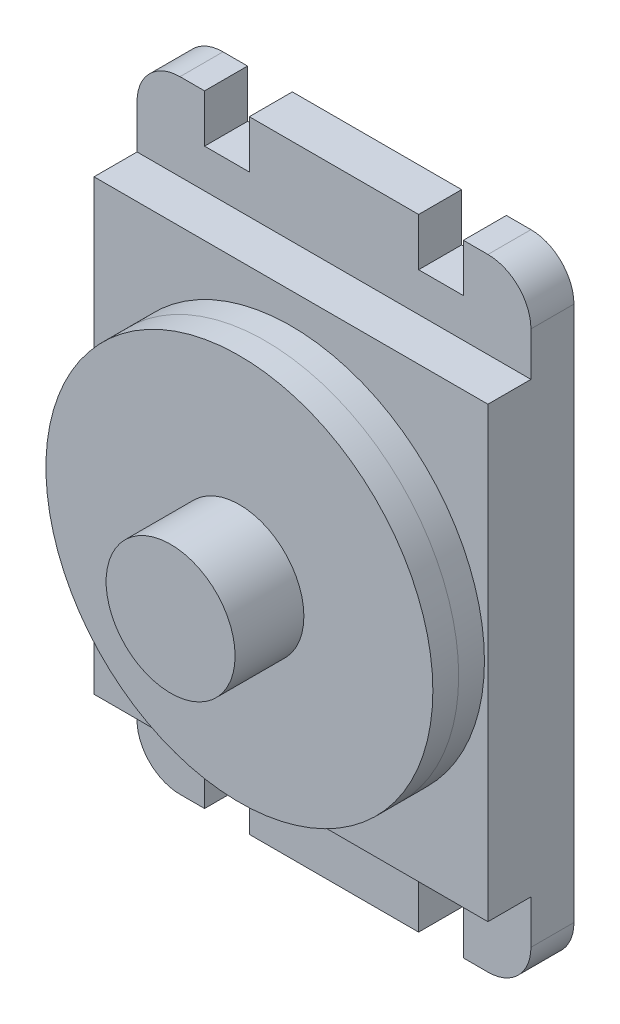
SolidWorks part; units mm, degrees
ref_plane "Front Plane" through (0, 0, 0) normal (0, 0, 1) x (1, 0, 0)
ref_plane "Top Plane" through (0, 0, 0) normal (0, 1, 0) x (1, 0, 0)
ref_plane "Right Plane" through (0, 0, 0) normal (1, 0, 0) x (0, 0, -1)
sketch "Sketch1" plane through (0, 0, 0) normal (0, 0, 1) x (1, 0, 0)
  line L0 (-70.0486, 36.1417) -> (-70.0486, 30.5715)
  line L1 (-72.9051, 36.1417) -> (-70.0486, 36.1417)
  line L2 (-77.9051, 31.1417) -> (-77.9051, -31.1417)
  line L3 (-72.9051, -36.1417) -> (-70.0486, -36.1417)
  line L4 (-32.0949, 31.1417) -> (-32.0949, -31.1417)
  line L5 (-77.9051, 36.1417) -> (-32.0949, -36.1417) construction
  line L6 (-77.9051, -36.1417) -> (-32.0949, 36.1417) construction
  line L7 (-70.0486, 30.5715) -> (-64.8452, 30.5715)
  line L8 (-64.8452, 30.5715) -> (-64.8452, 36.1417)
  line L9 (-55, 34.9348) -> (-55, -34.9348) construction
  line L10 (-77.9051, 0) -> (-32.0949, 0) construction
  line L11 (-64.8452, 36.1417) -> (-45.1548, 36.1417)
  line L12 (-45.1548, 30.5715) -> (-45.1548, 36.1417)
  line L13 (-39.9514, 30.5715) -> (-45.1548, 30.5715)
  line L14 (-39.9514, 30.5715) -> (-39.9514, 36.1417)
  line L15 (-64.8452, -30.5715) -> (-64.8452, -36.1417)
  line L16 (-70.0486, -30.5715) -> (-64.8452, -30.5715)
  line L17 (-70.0486, -36.1417) -> (-70.0486, -30.5715)
  line L18 (-39.9514, -36.1417) -> (-39.9514, -30.5715)
  line L19 (-39.9514, -30.5715) -> (-45.1548, -30.5715)
  line L20 (-45.1548, -30.5715) -> (-45.1548, -36.1417)
  line L21 (-64.8452, -36.1417) -> (-45.1548, -36.1417)
  line L22 (-39.9514, -36.1417) -> (-37.0949, -36.1417)
  line L23 (-39.9514, 36.1417) -> (-37.0949, 36.1417)
  arc A0 (-32.0949, -31.1417) -> (-37.0949, -36.1417) centre (-37.0949, -31.1417) cw
  arc A1 (-77.9051, -31.1417) -> (-72.9051, -36.1417) centre (-72.9051, -31.1417) ccw
  arc A2 (-32.0949, 31.1417) -> (-37.0949, 36.1417) centre (-37.0949, 31.1417) ccw
  arc A3 (-72.9051, 36.1417) -> (-77.9051, 31.1417) centre (-72.9051, 31.1417) ccw
  point P0 (-55, 0)
  dimension "D1" = 5
extrude "Boss-Extrude1" add sketch "Sketch1" along normal blind 5
sketch "Sketch2" plane through (0, 0, 5) normal (0, 0, 1) x (1, 0, 0)
  line L0 (-32.0949, -31.1417) -> (-32.0949, 31.1417) construction
  line L1 (-77.9051, 26.0595) -> (-32.0949, 26.0595)
  line L2 (-77.9051, 26.0595) -> (-77.9051, -26.0595)
  line L3 (-77.9051, -26.0595) -> (-32.0949, -26.0595)
  line L4 (-32.0949, 26.0595) -> (-32.0949, -26.0595)
  line L5 (-77.9051, 26.0595) -> (-32.0949, -26.0595) construction
  line L6 (-77.9051, -26.0595) -> (-32.0949, 26.0595) construction
  point P0 (-55, 0)
extrude "Boss-Extrude2" add sketch "Sketch2" along normal blind 5
sketch "Sketch3" plane through (0, 0, 10) normal (0, 0, 1) x (1, 0, 0)
  circle A0 centre (-55, 0) radius 22.5
extrude "Boss-Extrude3" add sketch "Sketch3" along normal blind 3
sketch "Sketch4" plane through (0, 0, 13) normal (0, 0, 1) x (1, 0, 0)
  circle A0 centre (-55, 0) radius 22.5
extrude "Boss-Extrude4" add sketch "Sketch4" along normal blind 3 separate body
sketch "Sketch5" plane through (0, 0, 16) normal (0, 0, 1) x (1, 0, 0)
  circle A0 centre (-55, 0) radius 7.5
extrude "Boss-Extrude5" add sketch "Sketch5" along normal blind 8
sketch "Sketch6" plane through (0, 0, 0) normal (0, 0, -1) x (-1, 0, 0)
  line L0 (55, 36.1417) -> (55, -36.1417) construction
  line L1 (45.1548, 36.1417) -> (64.8452, 36.1417) construction
  line L2 (64.8452, -36.1417) -> (45.1548, -36.1417) construction
  line L3 (32.0949, -31.1417) -> (32.0949, 31.1417) construction
  line L4 (77.9051, 31.1417) -> (77.9051, -31.1417) construction
  circle A0 centre (42.0949, 16.1417) radius 2.5
  circle A1 centre (67.9051, -16.1417) radius 2.5
  dimension "D2" = 10
  dimension "D3" = 5
  dimension "D4" = 20
  dimension "D5" = 10
  dimension "D6" = 5
  dimension "D1" = 20
extrude "Boss-Extrude6" add sketch "Sketch6" along normal blind 5
